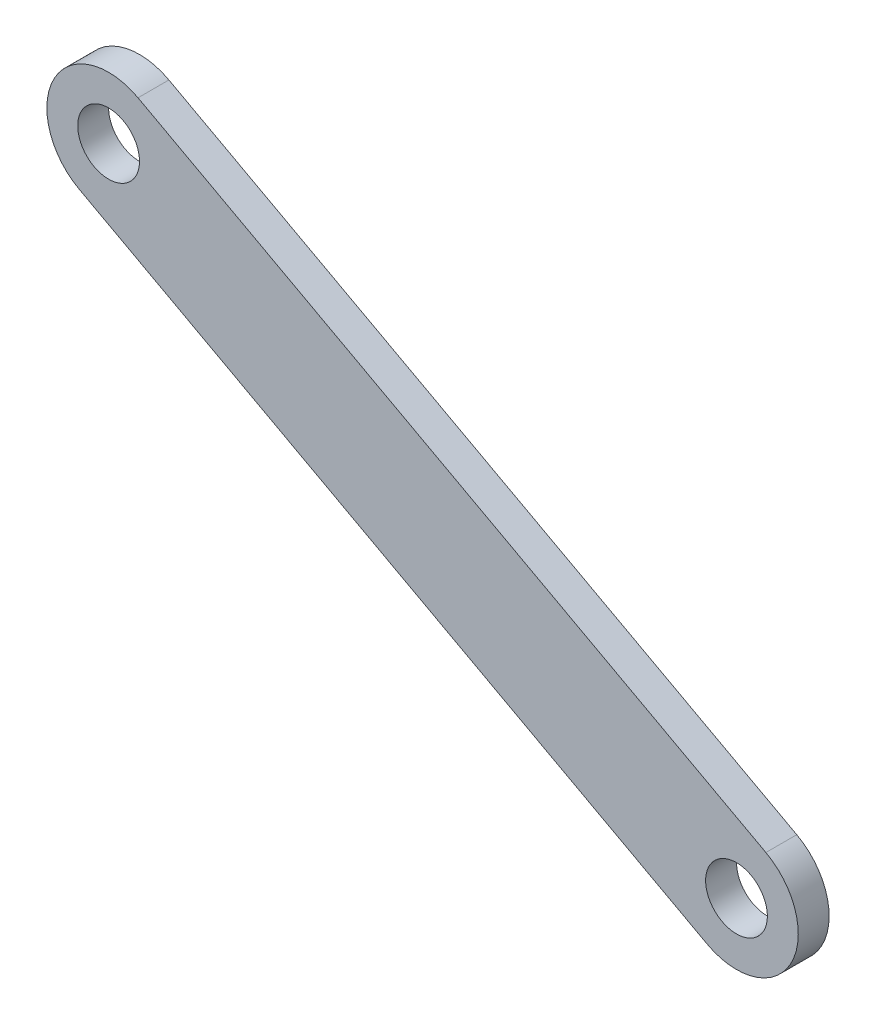
SolidWorks part; units mm, degrees
ref_plane "Front" through (0, 0, 0) normal (0, 0, 1) x (1, 0, 0)
ref_plane "Top" through (0, 0, 0) normal (0, 1, 0) x (1, 0, 0)
ref_plane "Right" through (0, 0, 0) normal (1, 0, 0) x (0, 0, -1)
sketch "Sketch1" plane through (0, 0, 0) normal (0, 0, 1) x (1, 0, 0)
  line L0 (-59.2315, -28.0529) -> (-26.9521, -45.5152) construction
  line L1 (-57.7208, -25.2604) -> (-25.4414, -42.7226)
  line L2 (-60.7422, -30.8455) -> (-28.4628, -48.3077)
  arc A0 (-57.7208, -25.2604) -> (-60.7422, -30.8455) centre (-59.2315, -28.0529) ccw
  arc A1 (-28.4628, -48.3077) -> (-25.4414, -42.7226) centre (-26.9521, -45.5152) ccw
  circle A2 centre (-26.9521, -45.5152) radius 1.5875
  circle A3 centre (-59.2315, -28.0529) radius 1.5875
  point P4 (-43.0918, -36.7841)
  dimension "D1" = 3.175
  dimension "D2" = 6.35
extrude "Boss-Extrude1" add sketch "Sketch1" along normal blind 1.5875 from offset 1.5875 offset against normal yes
